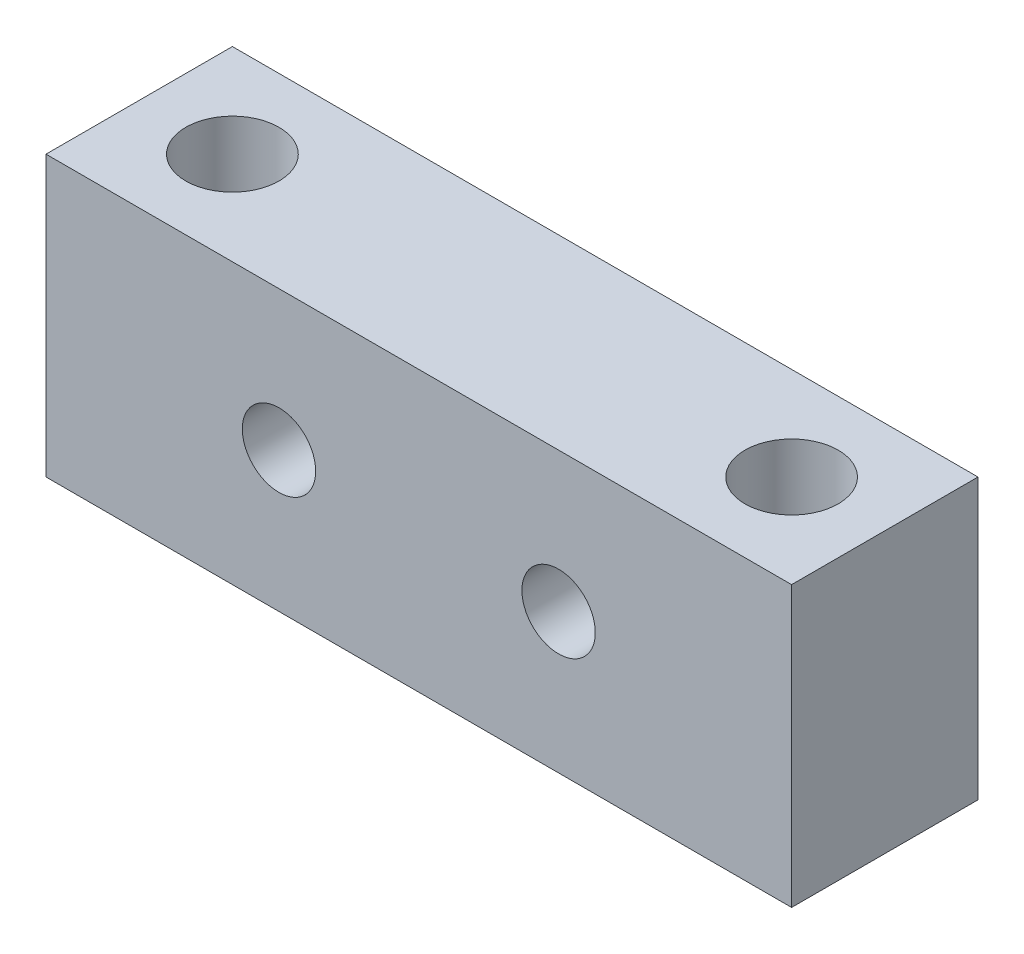
SolidWorks part; units mm, degrees
material "6061 Alloy"
ref_plane "Front Plane" through (0, 0, 0) normal (0, 0, 1) x (1, 0, 0)
ref_plane "Top Plane" through (0, 0, 0) normal (0, 1, 0) x (1, 0, 0)
ref_plane "Right Plane" through (0, 0, 0) normal (1, 0, 0) x (0, 0, -1)
sketch "Sketch1" plane through (0, 0, 0) normal (0, 0, 1) x (1, 0, 0)
  line L1 (-25.4, 9.525) -> (25.4, 9.525)
  line L2 (-25.4, 9.525) -> (-25.4, -9.525)
  line L3 (-25.4, -9.525) -> (25.4, -9.525)
  line L4 (25.4, 9.525) -> (25.4, -9.525)
  line L5 (-25.4, 9.525) -> (25.4, -9.525) construction
  line L6 (-25.4, -9.525) -> (25.4, 9.525) construction
  point P0 (0, 0)
  dimension "D1" = 50.8
  dimension "D2" = 19.05
extrude "Boss-Extrude1" add sketch "Sketch1" along normal blind 12.7
sketch "Sketch2" plane through (0, 0, 12.7) normal (0, 0, 1) x (1, 0, 0)
  line L0 (0, 9.525) -> (0, -9.525) construction
  line L1 (25.4, 9.525) -> (-25.4, 9.525) construction
  line L2 (-25.4, -9.525) -> (25.4, -9.525) construction
  line L3 (-25.4, 9.525) -> (-25.4, -9.525) construction
  circle A0 centre (-9.525, 0) radius 2.5
  circle A1 centre (9.525, 0) radius 2.5
  dimension "D2" = 5
  dimension "D3" = 9.525
  dimension "D1" = 15.875
extrude "Cut-Extrude1" cut sketch "Sketch2" against normal through all
sketch "Sketch3" plane through (0, 9.525, 0) normal (0, 1, 0) x (1, 0, 0)
  line L0 (0, 4.2472) -> (0, -15.9331) construction
  line L1 (25.4, 0) -> (-25.4, 0) construction
  line L2 (-25.4, -12.7) -> (-25.4, 0) construction
  circle A0 centre (-19.05, -6.35) radius 3.175
  circle A1 centre (19.05, -6.35) radius 3.175
  dimension "D3" = 6.35
  dimension "D1" = 6.35
  dimension "D2" = 6.35
extrude "Cut-Extrude2" cut sketch "Sketch3" against normal through all
